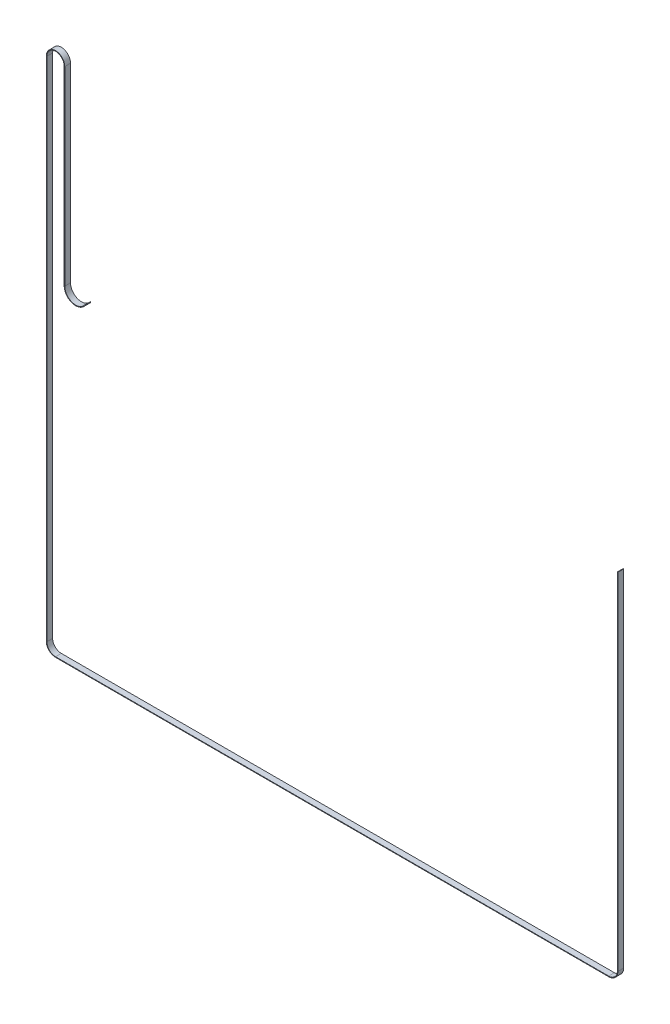
SolidWorks part; units mm, degrees
ref_plane "Ebene vorne" through (0, 0, 0) normal (0, 0, 1) x (1, 0, 0)
ref_plane "Ebene oben" through (0, 0, 0) normal (0, 1, 0) x (1, 0, 0)
ref_plane "Ebene rechts" through (0, 0, 0) normal (1, 0, 0) x (0, 0, -1)
sketch "Skizze1" plane through (0, 0, 0) normal (0, 0, 1) x (1, 0, 0)
  line L0 (-240, 0) -> (240, 0) construction
  line L1 (-240, 0) -> (-240, 440) construction
  line L2 (240, 0) -> (240, 300) construction
  line L3 (-232.5, 440) -> (-232.5, 275)
  line L4 (240, -7.5) -> (-240, -7.5)
  line L5 (-247.5, 0) -> (-247.5, 440)
  line L6 (247.5, 0) -> (247.5, 300)
  circle A0 centre (-240, 440) radius 7.5 construction
  circle A1 centre (-240, 0) radius 7.5 construction
  circle A2 centre (240, 0) radius 7.5 construction
  circle A3 centre (-222.5, 275) radius 10 construction
  arc A4 (-232.5, 440) -> (-247.5, 440) centre (-240, 440) ccw
  arc A5 (-247.5, 0) -> (-240, -7.5) centre (-240, 0) ccw
  arc A6 (247.5, 0) -> (240, -7.5) centre (240, 0) cw
  arc A7 (-232.5, 275) -> (-214.4376, 269.0841) centre (-222.5, 275) ccw
  dimension "D4" = 15
  dimension "D5" = 20
  dimension "D1" = 480
  dimension "D2" = 440
  dimension "D3" = 300
  dimension "D6" = 165
  dimension "D7" = 17.5
extrude "Linear-Austragen-Dünn1" add sketch "Skizze1" along normal mid plane 5 thin thin type one direction reverse wall 0.5
